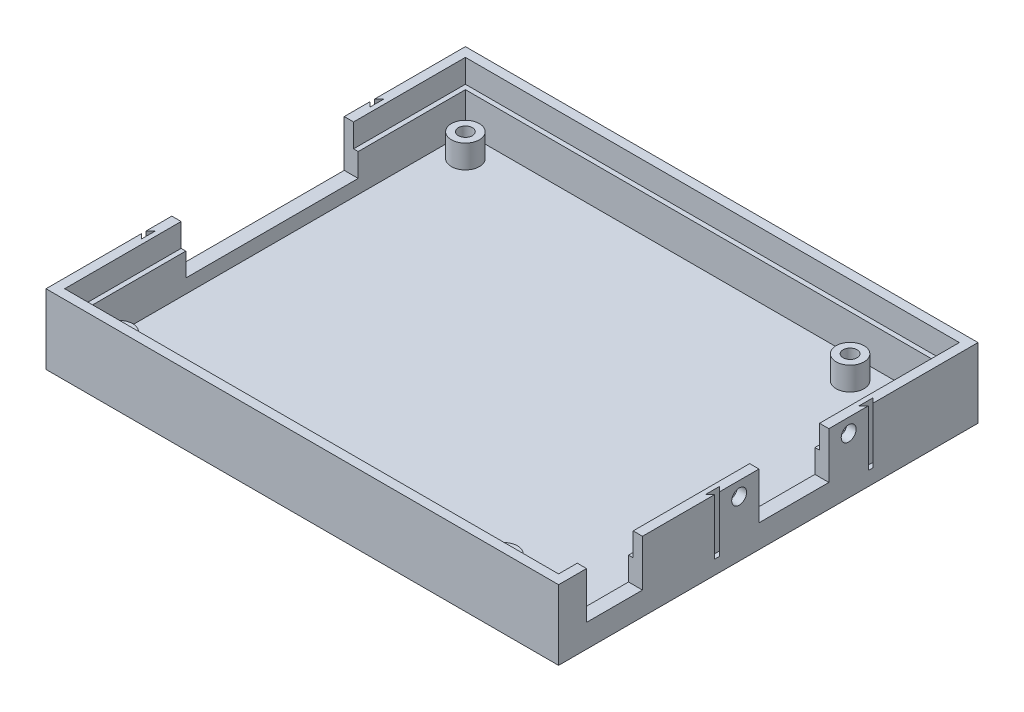
SolidWorks part; units mm, degrees
ref_plane "Alzado" through (0, 0, 0) normal (0, 0, 1) x (1, 0, 0)
ref_plane "Planta" through (0, 0, 0) normal (0, 1, 0) x (1, 0, 0)
ref_plane "Vista lateral" through (0, 0, 0) normal (1, 0, 0) x (0, 0, -1)
sketch "Croquis1" plane through (0, 0, 0) normal (0, 1, 0) x (1, 0, 0)
  line L1 (-51, -41) -> (51, -41) construction
  line L2 (-51, -41) -> (-51, 41) construction
  line L3 (-51, 41) -> (51, 41) construction
  line L4 (51, -41) -> (51, 41) construction
  line L5 (-51, -41) -> (51, 41) construction
  line L6 (-51, 41) -> (51, -41) construction
  line L7 (-55, -45) -> (55, -45)
  line L8 (-55, -45) -> (-55, 45)
  line L9 (-55, 45) -> (55, 45)
  line L10 (55, -45) -> (55, 45)
  line L11 (-55, -45) -> (55, 45) construction
  line L12 (-55, 45) -> (55, -45) construction
  point P0 (0, 0)
  point P6 (0, 0)
  dimension "D1" = 82
  dimension "D2" = 102
  dimension "D3" = 4
  dimension "D4" = 4
extrude "Saliente-Extruir1" add sketch "Croquis1" along normal blind 2
sketch "Croquis3" plane through (0, 2, 0) normal (0, 1, 0) x (1, 0, 0)
  line L0 (0, 0) -> (-51, 0) construction
  line L1 (-51, -41) -> (51, -41) construction
  line L2 (-51, -41) -> (-51, 41) construction
  line L3 (-51, 41) -> (51, 41) construction
  line L4 (51, -41) -> (51, 41) construction
  line L5 (-51, -41) -> (51, 41) construction
  line L6 (-51, 41) -> (51, -41) construction
  circle A0 centre (-47.19, -37.19) radius 3
  circle A1 centre (-47.19, 37.19) radius 3
  circle A2 centre (35.36, -37.19) radius 3
  circle A3 centre (35.36, 37.19) radius 3
  point P0 (0, 0)
  dimension "D3" = 6
  dimension "D4" = 3.81
  dimension "D5" = 3.81
  dimension "D6" = 6
  dimension "D7" = 86.36
  dimension "D8" = 3.81
  dimension "D1" = 82
  dimension "D2" = 102
extrude "Saliente-Extruir2" add sketch "Croquis3" along normal blind 5
sketch "Croquis4" plane through (0, 7, 0) normal (0, 1, 0) x (1, 0, 0)
  circle A0 centre (-47.19, -37.19) radius 1.5
  circle A1 centre (35.36, -37.19) radius 1.5
  circle A2 centre (35.36, 37.19) radius 1.5
  circle A3 centre (-47.19, 37.19) radius 1.5
  dimension "D1" = 3
  dimension "D2" = 3
  dimension "D3" = 3
  dimension "D4" = 3
extrude "Cortar-Extruir1" cut sketch "Croquis4" against normal blind 4
sketch "Croquis5" plane through (0, 2, 0) normal (0, 1, 0) x (1, 0, 0)
  line L0 (52, -39) -> (55, -39)
  line L1 (-55, -45) -> (55, -45)
  line L2 (-55, -45) -> (-55, -18)
  line L3 (-55, 45) -> (55, 45)
  line L4 (55, -45) -> (55, -39)
  line L5 (-55, -45) -> (55, 45) construction
  line L6 (-55, 45) -> (55, -45) construction
  line L7 (-52, -42) -> (52, -42)
  line L8 (-52, -42) -> (-52, -18)
  line L9 (-52, 42) -> (52, 42)
  line L10 (52, -42) -> (52, -39)
  line L11 (-52, -42) -> (52, 42) construction
  line L12 (-52, 42) -> (52, -42) construction
  line L13 (52, -27) -> (55, -27)
  line L14 (52, 13) -> (55, 13)
  line L15 (52, -2) -> (55, -2)
  line L16 (52, 13) -> (52, 42)
  line L17 (55, 13) -> (55, 45)
  line L18 (52, -27) -> (52, -2)
  line L19 (55, -27) -> (55, -2)
  line L20 (-52, -18) -> (-55, -18)
  line L21 (-55, 19) -> (-52, 19)
  line L22 (-52, 19) -> (-52, 42)
  line L23 (-55, 19) -> (-55, 45)
  point P0 (0, 0)
  point P7 (0, 0)
  dimension "D1" = 3
  dimension "D2" = 3
  dimension "D3" = 3
  dimension "D4" = 15
  dimension "D5" = 40
  dimension "D6" = 55
  dimension "D7" = 24
  dimension "D8" = 61
extrude "Saliente-Extruir3" add sketch "Croquis5" along normal blind 13
sketch "Croquis6" plane through (0, 2, 0) normal (0, 1, 0) x (1, 0, 0)
  line L0 (55, -27) -> (55, -2) construction
  line L1 (-52, 19) -> (-55, 19)
  line L2 (-52, 19) -> (-52, -18)
  line L3 (-52, -18) -> (-55, -18)
  line L4 (-55, 19) -> (-55, -18)
  line L5 (52, 13) -> (55, 13)
  line L6 (52, 13) -> (52, -2)
  line L7 (52, -2) -> (55, -2)
  line L8 (55, 13) -> (55, -2)
  line L9 (55, -2) -> (52, -2) construction
  line L11 (52, -27) -> (55, -27)
  line L12 (52, -27) -> (52, -39)
  line L13 (52, -39) -> (55, -39)
  line L14 (55, -27) -> (55, -39)
extrude "Saliente-Extruir4" add sketch "Croquis6" along normal blind 3
sketch "Croquis7" plane through (0, 15, 0) normal (0, 1, 0) x (1, 0, 0)
  line L0 (-53, -43) -> (-53, 43)
  line L1 (-52, -42) -> (52, -42)
  line L2 (-52, -42) -> (-52, 42)
  line L3 (-52, 42) -> (52, 42)
  line L4 (52, -42) -> (52, 42)
  line L5 (-53, 43) -> (53, 43)
  line L6 (53, -43) -> (53, 43)
  line L7 (-53, -43) -> (53, -43)
  dimension "D1" = 1
extrude "Cortar-Extruir2" cut sketch "Croquis7" against normal blind 5
sketch "Croquis8" plane through (0, 15, 0) normal (0, 1, 0) x (1, 0, 0)
  line L0 (55, -27) -> (55, -2) construction
  line L1 (55, -10.5) -> (54, -9.5)
  line L2 (54, -9.5) -> (54, -12.5)
  line L3 (54, -12.5) -> (55, -11.5)
  line L4 (55, -11.5) -> (55, -10.5)
  line L5 (54, -11) -> (55, -11) construction
  line L6 (52, -2) -> (55, -2) construction
  line L7 (55, 5.5) -> (52, 5.5) construction
  line L8 (55, -2) -> (55, 13) construction
  line L9 (52, 42) -> (52, -42) construction
  line L10 (54, 22) -> (55, 22) construction
  line L11 (55, 22.5) -> (55, 21.5)
  line L12 (54, 23.5) -> (55, 22.5)
  line L13 (54, 20.5) -> (54, 23.5)
  line L14 (55, 21.5) -> (54, 20.5)
  point P5 (54, -11)
  dimension "D1" = 1
  dimension "D2" = 1
  dimension "D3" = 45
  dimension "D4" = 9
extrude "Cortar-Extruir3" cut sketch "Croquis8" against normal blind 12
sketch "Croquis9" plane through (55, 0, 0) normal (1, 0, 0) x (0, 0, -1)
  line L0 (-10.5, 15) -> (-2, 15) construction
  line L1 (-6.25, 12) -> (-6.25, 15) construction
  line L2 (5.5, 5) -> (5.5, 15) construction
  line L3 (-2, 5) -> (13, 5) construction
  circle A0 centre (-6.25, 12) radius 1.6
  circle A1 centre (17.25, 12) radius 1.6
  dimension "D1" = 3.2
  dimension "D2" = 3
extrude "Cortar-Extruir4" cut sketch "Croquis9" against normal blind 12
sketch "Croquis11" plane through (0, 15, 0) normal (0, 1, 0) x (1, 0, 0)
  line L0 (-55, -23.5) -> (-54, -22.5)
  line L1 (-55, -18) -> (-55, -45) construction
  line L2 (-54, -22.5) -> (-54, -25.5)
  line L3 (-54, -25.5) -> (-55, -24.5)
  line L4 (-55, -24.5) -> (-55, -23.5)
  line L5 (-55, -24) -> (-54, -24) construction
  line L6 (-55, 0.5) -> (-52, 0.5) construction
  line L7 (-55, 19) -> (-55, -18) construction
  line L8 (-52, -18) -> (-52, 19) construction
  line L9 (-55, -18) -> (-52, -18) construction
  line L10 (-55, 25) -> (-54, 25) construction
  line L11 (-55, 25.5) -> (-55, 24.5)
  line L12 (-54, 26.5) -> (-55, 25.5)
  line L13 (-54, 23.5) -> (-54, 26.5)
  line L14 (-55, 24.5) -> (-54, 23.5)
  dimension "D1" = 1
  dimension "D2" = 1
  dimension "D3" = 45
  dimension "D4" = 45
  dimension "D5" = 6
extrude "Cortar-Extruir5" cut sketch "Croquis11" against normal blind 12
equation "\"D2@Croquis4\"=\"D1@Croquis4\""
equation "\"D3@Croquis4\"=\"D1@Croquis4\""
equation "\"D4@Croquis4\"=\"D1@Croquis4\""
